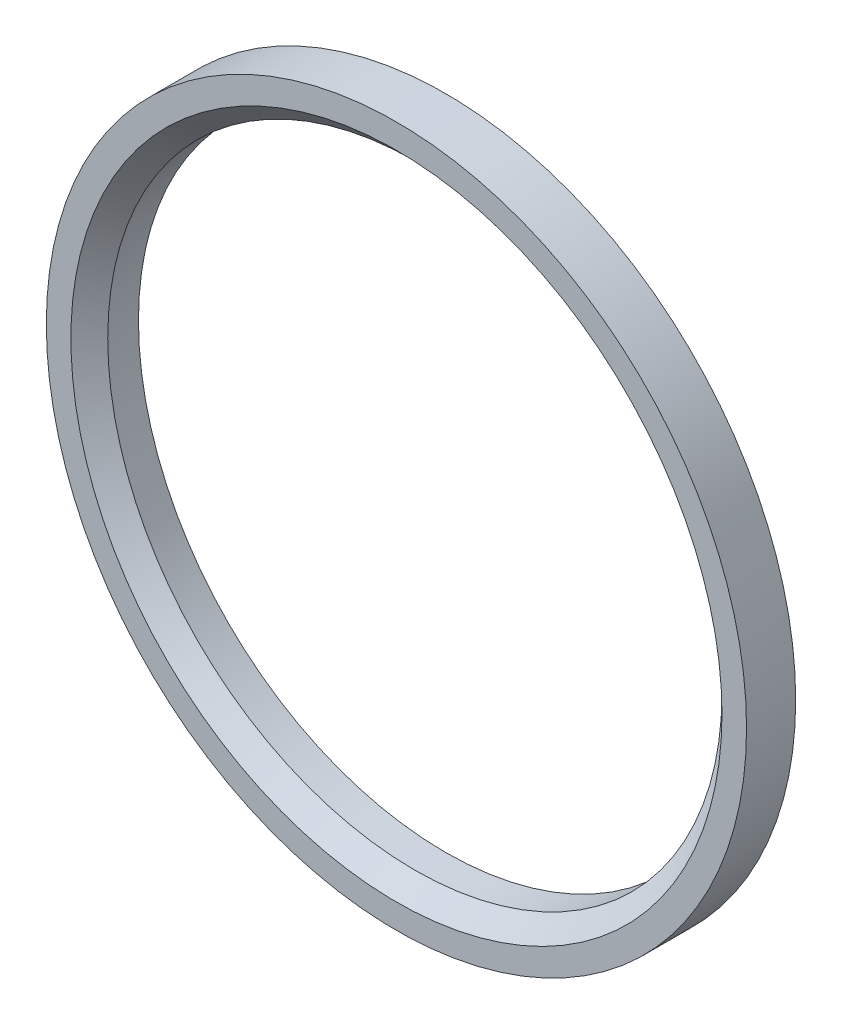
SolidWorks part; units mm, degrees
ref_plane "Przednia" through (0, 0, 0) normal (0, 0, 1) x (1, 0, 0)
ref_plane "Górna" through (0, 0, 0) normal (0, 1, 0) x (1, 0, 0)
ref_plane "Prawa" through (0, 0, 0) normal (1, 0, 0) x (0, 0, -1)
sketch "Szkic2" plane through (0, 0, 0) normal (0, 0, 1) x (1, 0, 0)
  circle A0 centre (0, 0) radius 28.5
  circle A1 centre (0, 0) radius 25
  dimension "D1" = 57
  dimension "D2" = 50
extrude "Dodanie-wyciągnięcie2" add sketch "Szkic2" along normal mid plane 4
chamfer "Sfazowanie1" distance 1.5 angle 45 1 edges at (25, 0, 2)
